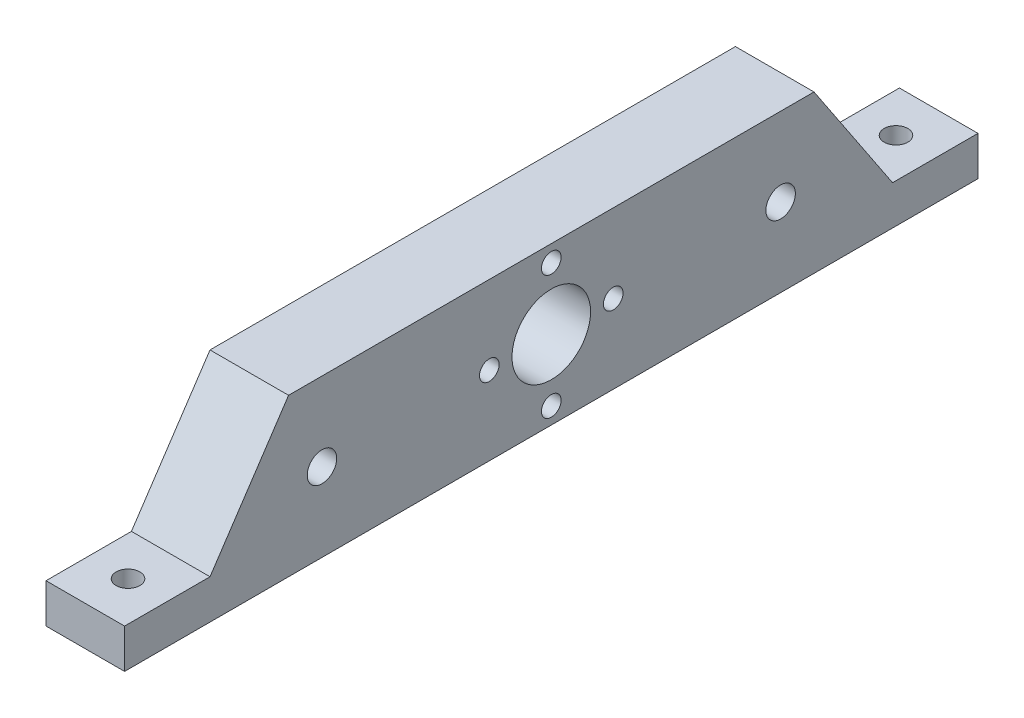
SolidWorks part; units mm, degrees
ref_plane "Front Plane" through (0, 0, 0) normal (0, 0, 1) x (1, 0, 0)
ref_plane "Top Plane" through (0, 0, 0) normal (0, 1, 0) x (1, 0, 0)
ref_plane "Right Plane" through (0, 0, 0) normal (1, 0, 0) x (0, 0, -1)
sketch "Sketch2" plane through (0, 0, 0) normal (1, 0, 0) x (0, 0, -1)
  line L1 (0, 0) -> (380, 0)
  line L2 (0, 0) -> (0, 40)
  line L3 (0, 40) -> (380, 40)
  line L4 (380, 0) -> (380, 40)
  line L5 (190, 0) -> (275.0005, 0)
  circle A2 centre (190, 20) radius 10
  circle A3 centre (131.63, 20) radius 3.75
  circle A4 centre (248.37, 20) radius 3.75
  dimension "D1" = 20
extrude "Boss-Extrude2" add sketch "Sketch2" along normal blind 20
sketch "Sketch3" plane through (0, 0, 0) normal (-1, 0, 0) x (0, 0, 1)
  line L0 (-190, 20) -> (-131.635, 20)
  line L1 (-190, 20) -> (-248.365, 20)
  dimension "D1" = 58.365
  dimension "D2" = 58.365
sketch "Sketch4" plane through (20, 0, 0) normal (1, 0, 0) x (0, 0, -1)
  line L1 (0, 0) -> (380, 0) construction
  line L3 (0, 40) -> (380, 40) construction
  line L4 (123.1292, 40) -> (0, 40)
  line L5 (0, 40) -> (0, 0)
  line L7 (103.136, 10) -> (123.1292, 40)
  line L12 (103.136, 10) -> (81.389, 10)
  line L13 (81.389, 10) -> (81.389, 0)
  line L14 (81.389, 0) -> (0, 0)
  line L16 (298.611, 10) -> (298.611, 0)
  line L17 (276.864, 10) -> (298.611, 10)
  line L18 (276.864, 10) -> (256.8708, 40)
  line L19 (256.8708, 40) -> (380, 40)
  line L20 (380, 40) -> (380, 0)
  line L21 (298.611, 0) -> (380, 0)
extrude "Cut-Extrude1" cut sketch "Sketch4" against normal blind 100
sketch "Sketch5" plane through (0, 10, 0) normal (0, 1, 0) x (1, 0, 0)
  circle A0 centre (10, 92.2625) radius 3.0234
  circle A1 centre (10, 287.7375) radius 3.0234
extrude "Cut-Extrude2" cut sketch "Sketch5" against normal through all both and the other way through all
sketch "Sketch8" plane through (20, 0, 0) normal (1, 0, 0) x (0, 0, -1)
  line L1 (81.389, 0) -> (298.611, 0) construction
  line L7 (170, 20) -> (210, 20) construction
  line L9 (190, 0) -> (190, 40) construction
  circle A5 centre (190, 35.7651) radius 2.5
  circle A7 centre (190, 4.2349) radius 2.5
  circle A9 centre (174.23, 20) radius 2.5
  circle A11 centre (205.77, 20) radius 2.5
  point P19 (175.157, 20)
  point P20 (203.6221, 20)
  point P23 (206.2157, 22.7084)
extrude "Cut-Extrude3" cut sketch "Sketch8" against normal through all
